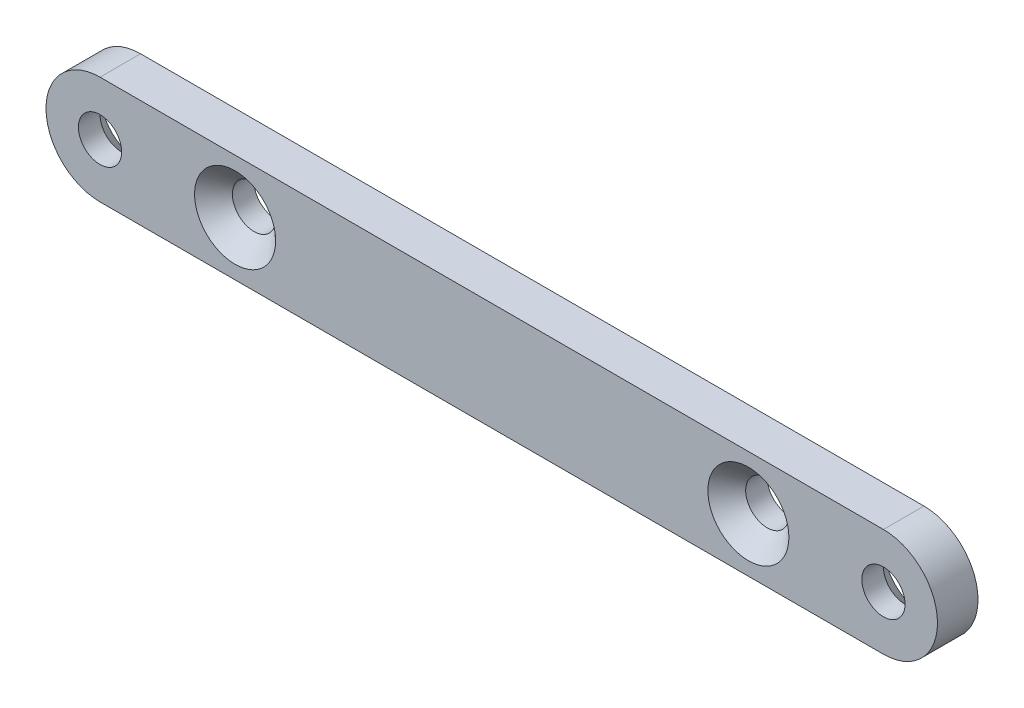
SolidWorks part; units mm, degrees
ref_plane "前视基准面" through (0, 0, 0) normal (0, 0, 1) x (1, 0, 0)
ref_plane "上视基准面" through (0, 0, 0) normal (0, 1, 0) x (1, 0, 0)
ref_plane "右视基准面" through (0, 0, 0) normal (1, 0, 0) x (0, 0, -1)
sketch "草图1" plane through (0, 0, 0) normal (0, 0, 1) x (1, 0, 0)
  line L0 (-10, 0) -> (48, 0) construction
  line L21 (-10, 4) -> (48, 4)
  line L22 (-10, -4) -> (48, -4)
  circle A0 centre (0, 0) radius 1.6
  circle A1 centre (38, 0) radius 1.6
  circle A6 centre (38.1712, 24) radius 1.6 [skipped]
  circle A7 centre (0.1712, 24) radius 1.6 [skipped]
  circle A8 centre (38.3424, 48) radius 1.6 [skipped]
  circle A9 centre (0.3424, 48) radius 1.6 [skipped]
  arc A10 (-10, 4) -> (-10, -4) centre (-10, 0) ccw
  arc A11 (48, -4) -> (48, 4) centre (48, 0) ccw
  circle A12 centre (-10, 0) radius 1.6
  circle A13 centre (48, 0) radius 1.6
  point P7 (19, 0)
  dimension "D1" = 3.2
  dimension "D4" = 38
  dimension "D5" = 10
  dimension "D6" = 10
  dimension "D7" = 4
  dimension "D2" = 2
  dimension "D3" = 3
extrude "凸台-拉伸1" add sketch "草图1" along normal blind 3
chamfer "倒角1" distance 1.4 angle 45 4 edges at (39.6, 0, 3) (1.6, 0, 3) (49.6, 0, 0) (-8.4, 0, 0)
